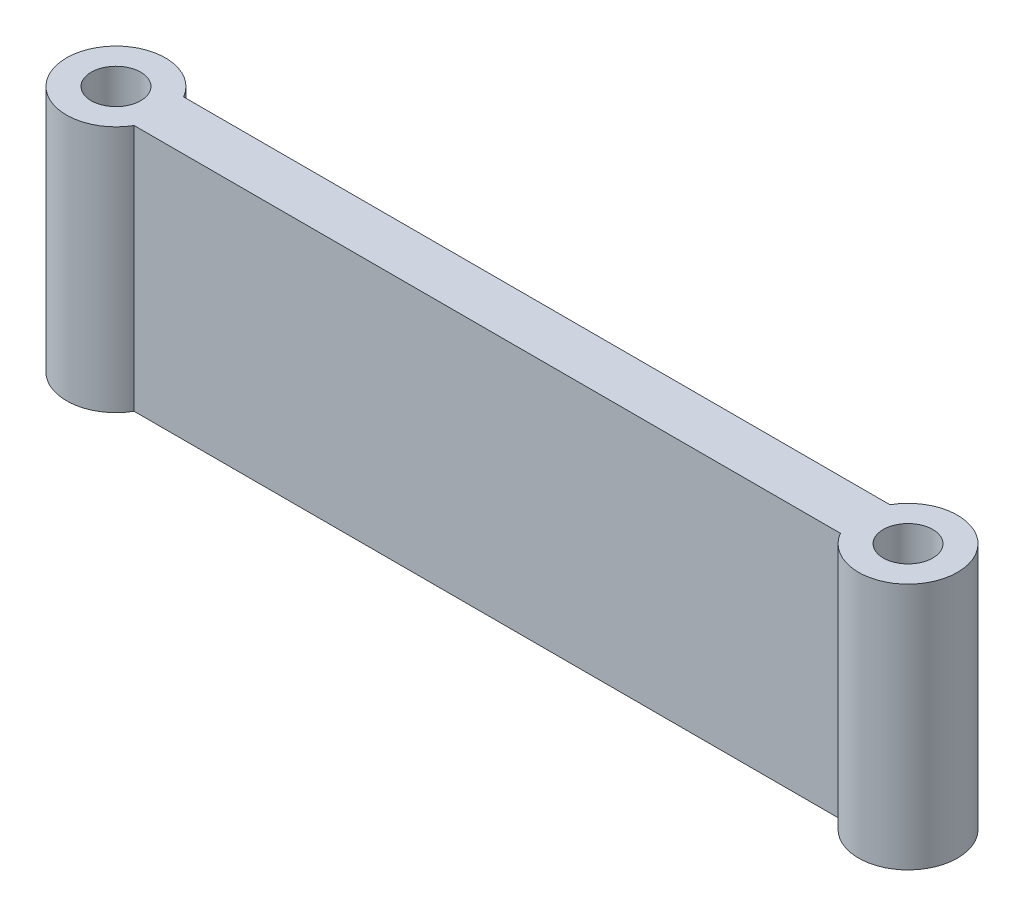
SolidWorks part; units mm, degrees
material "1023 Carbon Steel Sheet (SS)"
ref_plane "Front Plane" through (0, 0, 0) normal (0, 0, 1) x (1, 0, 0)
ref_plane "Top Plane" through (0, 0, 0) normal (0, 1, 0) x (1, 0, 0)
ref_plane "Right Plane" through (0, 0, 0) normal (1, 0, 0) x (0, 0, -1)
sketch "Sketch1" plane through (0, 0, 0) normal (0, 1, 0) x (1, 0, 0)
  line L1 (4.3301, -2.5) -> (75.6699, -2.5)
  line L3 (4.3301, 2.5) -> (75.6699, 2.5)
  arc A0 (4.3301, 2.5) -> (4.3301, -2.5) centre (0, 0) ccw
  arc A1 (75.6699, 2.5) -> (75.6699, -2.5) centre (80, 0) cw
  circle A2 centre (0, 0) radius 2.5
  circle A3 centre (80, 0) radius 2.5
  dimension "D1" = 10
  dimension "D2" = 5
  dimension "D3" = 80
  dimension "D4" = 5
extrude "Boss-Extrude1" add sketch "Sketch1" along normal mid plane 25
